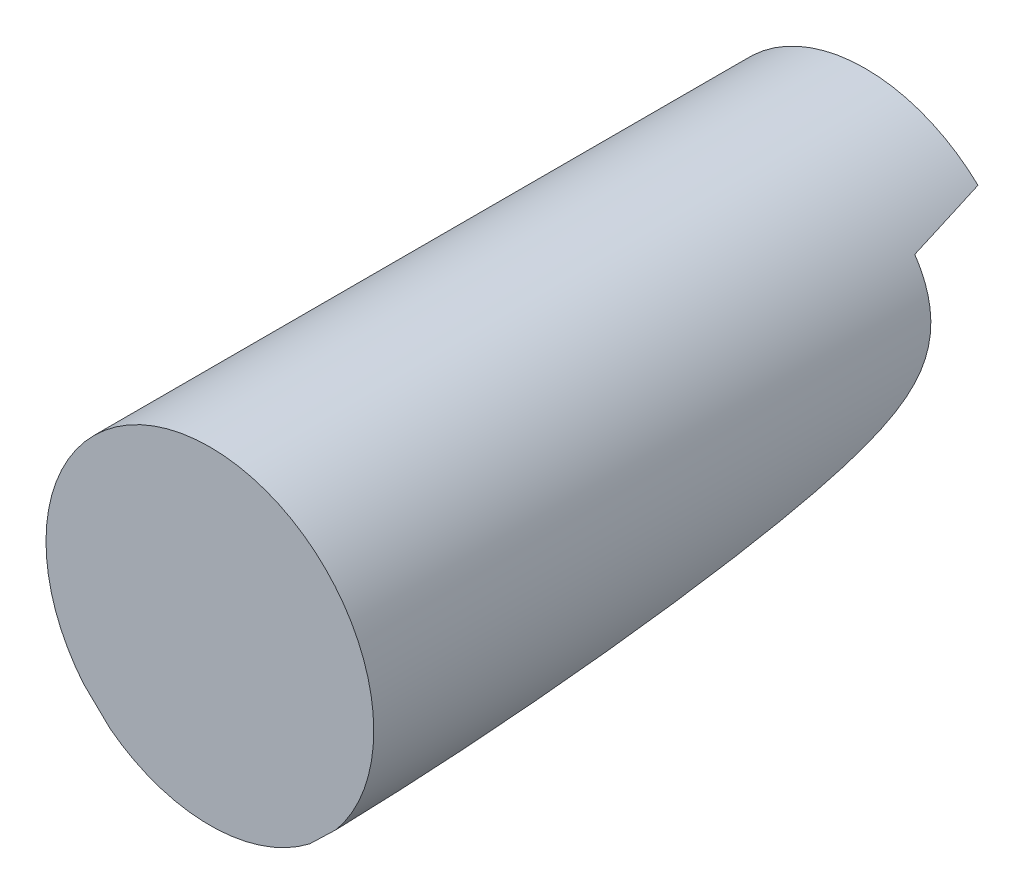
SolidWorks part; units mm, degrees
ref_plane "Front Plane" through (0, 0, 0) normal (0, 0, 1) x (1, 0, 0)
ref_plane "Top Plane" through (0, 0, 0) normal (0, 1, 0) x (1, 0, 0)
ref_plane "Right Plane" through (0, 0, 0) normal (1, 0, 0) x (0, 0, -1)
sketch "Sketch1" plane through (0, 0, 0) normal (0, 0, 1) x (1, 0, 0)
  line L0 (55, 0) -> (-55, 0) construction
  line L1 (0, -55) -> (0, 55) construction
  circle A0 centre (0, 0) radius 2.5
  dimension "D1" = 5
extrude "Boss-Extrude1" add sketch "Sketch1" along normal blind 10
sketch "Sketch3" plane through (0, 0, 0) normal (1, 0, 0) x (0, 0, -1)
  line L0 (-10, 0) -> (-0.4451, 0) construction
  line L1 (2.75, 0) -> (-2.75, 0) construction
  line L2 (-10, 2.5) -> (-10, -2.5) construction
  line L3 (-0.4451, 0) -> (-10.0119, -3.4542) construction
  dimension "D1" = 19.853
ref_plane "Plane1" through (0, -3.4542, 10.0119) normal (0, -0.3396, 0.9406) x (1, 0, 0)
sketch "Sketch5" plane through (0, -3.4542, 10.0119) normal (0, -0.3396, 0.9406) x (1, 0, 0)
  line L0 (0, 3.2449) -> (0, 0) construction
  line L1 (0, -4.7193) -> (0, 4.4169) construction
  line L2 (0, 0) -> (-1.9264, 1.7462)
  line L3 (0, 0) -> (1.9264, 1.7462)
  arc A0 (-1.9264, 1.7462) -> (1.9264, 1.7462) centre (0, 0) ccw
  ellipse E0 centre (0, 3.2449) end of major axis (2.5, 3.2449) minor radius 2.3514 construction
  dimension "sketch" = 5.2
extrude "Cut-Extrude2" cut sketch "Sketch5" against normal blind 12 contours A0 L3 L2
